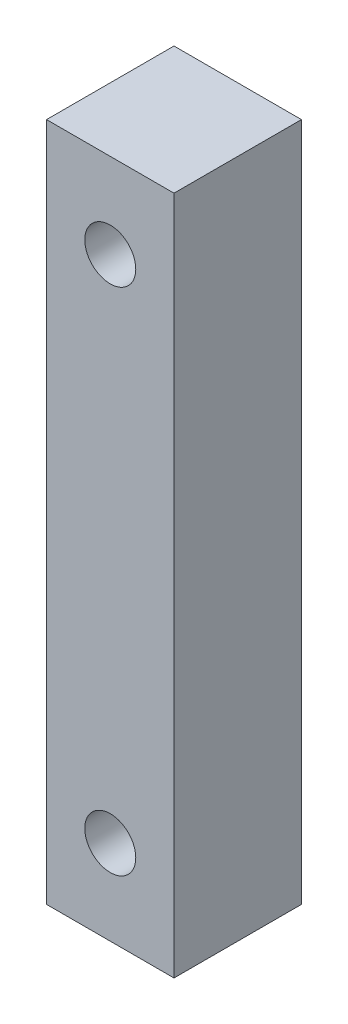
SolidWorks part; units mm, degrees
ref_plane "前视基准面" through (0, 0, 0) normal (0, 0, 1) x (1, 0, 0)
ref_plane "上视基准面" through (0, 0, 0) normal (0, 1, 0) x (1, 0, 0)
ref_plane "右视基准面" through (0, 0, 0) normal (1, 0, 0) x (0, 0, -1)
other "Configuration Table"
sketch "草图1" plane through (0, 0, 0) normal (0, 1, 0) x (1, 0, 0)
  line L1 (0, 0) -> (15, 0)
  line L2 (0, 0) -> (0, -15)
  line L3 (0, -15) -> (15, -15)
  line L4 (15, 0) -> (15, -15)
  dimension "D1" = 15
  dimension "D2" = 15
extrude "凸台-拉伸1" add sketch "草图1" along normal blind 80
sketch "草图2" plane through (0, 0, 15) normal (0, 0, 1) x (1, 0, 0)
  line L0 (7.5, 80) -> (7.5, 0) construction
  line L1 (0, 80) -> (15, 80) construction
  line L2 (0, 0) -> (15, 0) construction
  circle A0 centre (7.5, 70) radius 3
  circle A1 centre (7.5, 10) radius 3
  dimension "D2" = 6
  dimension "D3" = 6
  dimension "D1" = 60
  dimension "D4" = 10
extrude "切除-拉伸1" cut sketch "草图2" against normal through all
